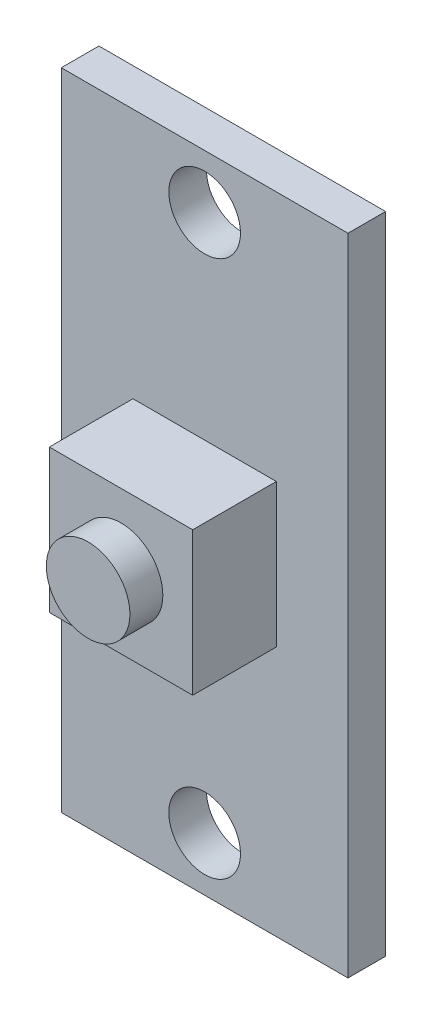
SolidWorks part; units mm, degrees
ref_plane "Front Plane" through (0, 0, 0) normal (0, 0, 1) x (1, 0, 0)
ref_plane "Top Plane" through (0, 0, 0) normal (0, 1, 0) x (1, 0, 0)
ref_plane "Right Plane" through (0, 0, 0) normal (1, 0, 0) x (0, 0, -1)
sketch "Sketch1" plane through (0, 0, 0) normal (0, 0, 1) x (1, 0, 0)
  line L1 (-6.096, -13.716) -> (6.096, -13.716)
  line L2 (-6.096, -13.716) -> (-6.096, 13.716)
  line L3 (-6.096, 13.716) -> (6.096, 13.716)
  line L4 (6.096, -13.716) -> (6.096, 13.716)
  line L5 (-6.096, -13.716) -> (6.096, 13.716) construction
  line L6 (-6.096, 13.716) -> (6.096, -13.716) construction
  point P0 (0, 0)
  dimension "D1" = 12.192
  dimension "D2" = 27.432
extrude "Boss-Extrude1" add sketch "Sketch1" along normal blind 1.6002
sketch "Sketch2" plane through (0, 0, 1.6002) normal (0, 0, 1) x (1, 0, 0)
  line L0 (-3.048, 3.048) -> (3.048, -3.048) construction
  line L7 (-3.048, 3.048) -> (3.048, 3.048)
  line L8 (-3.048, 3.048) -> (-3.048, -3.048)
  line L9 (-3.048, -3.048) -> (3.048, -3.048)
  line L10 (3.048, 3.048) -> (3.048, -3.048)
  point P0 (0, 0)
  dimension "D1" = 6.096
extrude "Boss-Extrude2" add sketch "Sketch2" along normal blind 3.556
sketch "Sketch4" plane through (0, 0, 1.6002) normal (0, 0, 1) x (1, 0, 0)
  line L0 (0, 11.43) -> (0, 13.716) construction
  line L3 (0, -13.716) -> (0, -11.43) construction
  line L4 (-6.096, -13.716) -> (6.096, -13.716) construction
  line L6 (6.096, 13.716) -> (-6.096, 13.716) construction
  circle A0 centre (0, 11.43) radius 1.524
  circle A1 centre (0, -11.43) radius 1.524
  point P0 (0, -5.0367)
  dimension "D1" = 3.048
  dimension "D2" = 2.286
extrude "Cut-Extrude1" cut sketch "Sketch4" against normal through all both and the other way through all
sketch "Sketch5" plane through (0, 0, 5.1562) normal (0, 0, 1) x (1, 0, 0)
  circle A0 centre (0, 0) radius 1.778
  dimension "D1" = 3.556
extrude "Boss-Extrude3" add sketch "Sketch5" along normal blind 1.3995
